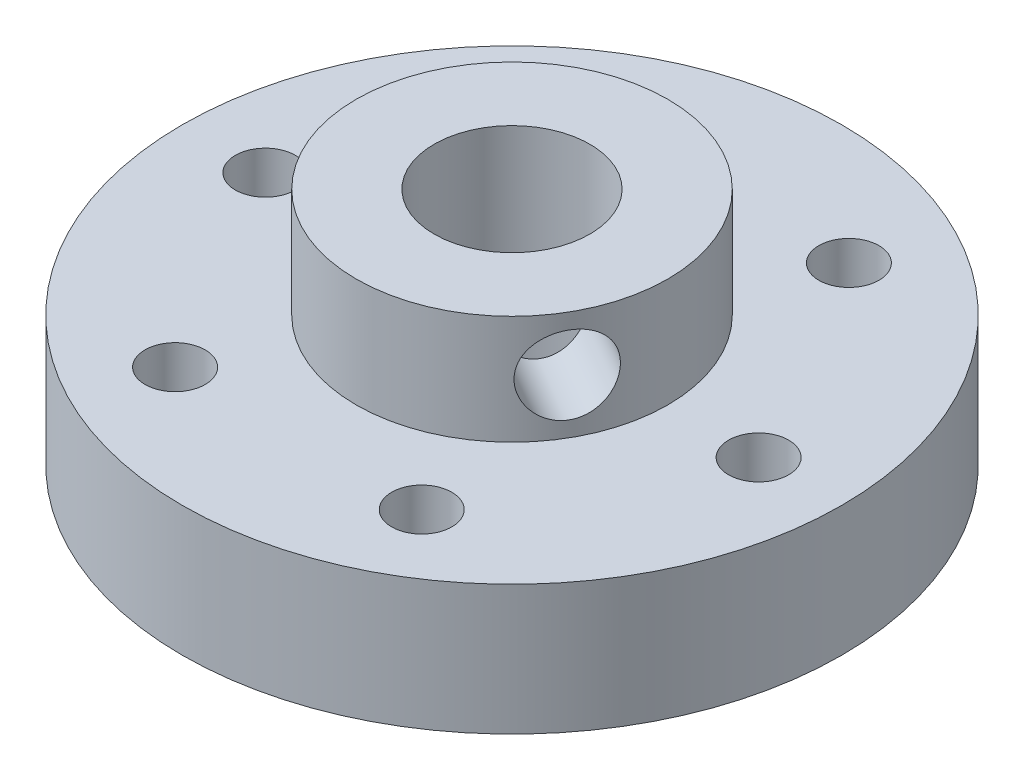
SolidWorks part; units mm, degrees
ref_plane "Front Plane" through (0, 0, 0) normal (0, 0, 1) x (1, 0, 0)
ref_plane "Top Plane" through (0, 0, 0) normal (0, 1, 0) x (1, 0, 0)
ref_plane "Right Plane" through (0, 0, 0) normal (1, 0, 0) x (0, 0, -1)
sketch "Sketch1" plane through (0, 0, 0) normal (0, 1, 0) x (1, 0, 0)
  circle A0 centre (0, 0) radius 12.7
  dimension "D1" = 25.4
extrude "Boss-Extrude1" add sketch "Sketch1" along normal blind 5
sketch "Sketch2" plane through (0, 5, 0) normal (0, 1, 0) x (1, 0, 0)
  circle A0 centre (0, 0) radius 6
  dimension "D1" = 12
extrude "Boss-Extrude2" add sketch "Sketch2" along normal blind 4.2
sketch "Sketch3" plane through (0, 9.2, 0) normal (0, 1, 0) x (1, 0, 0)
  circle A0 centre (0, 0) radius 3
  dimension "D1" = 6
extrude "Cut-Extrude1" cut sketch "Sketch3" against normal through all
sketch "Sketch5" plane through (0, 5, 0) normal (0, 1, 0) x (1, 0, 0)
  circle A0 centre (0, 0) radius 9.5 construction
  dimension "D1" = 19
sketch "Sketch6" plane through (0, 5, 0) normal (0, 1, 0) x (1, 0, 0)
  line L0 (0, 0) -> (-9.5, 0) construction
  circle A0 centre (0, 0) radius 9.5 construction
  circle A1 centre (-9.5, 0) radius 1.1582
  circle A2 centre (-4.75, 8.2272) radius 1.1582
  circle A3 centre (4.75, 8.2272) radius 1.1582
  circle A4 centre (9.5, 0) radius 1.1582
  circle A5 centre (4.75, -8.2272) radius 1.1582
  circle A6 centre (-4.75, -8.2272) radius 1.1582
  point P19 (0, 0)
  dimension "D1" = 6
extrude "Cut-Extrude2" cut sketch "Sketch6" against normal through all
ref_plane "Plane1" through (0, 5, 0) normal (-0.866, 0, -0.5) x (-0.5, 0, 0.866)
sketch "Sketch7" plane through (0, 5, 0) normal (-0.866, 0, -0.5) x (-0.5, 0, 0.866)
  line L0 (0, 0) -> (0, 2.1) construction
  line L1 (9.5, 0) -> (-9.5, 0) construction
  circle A0 centre (0, 2.1) radius 1.5
  dimension "D2" = 3
  dimension "D1" = 2.1
extrude "Cut-Extrude3" cut sketch "Sketch7" against normal blind 8.2
